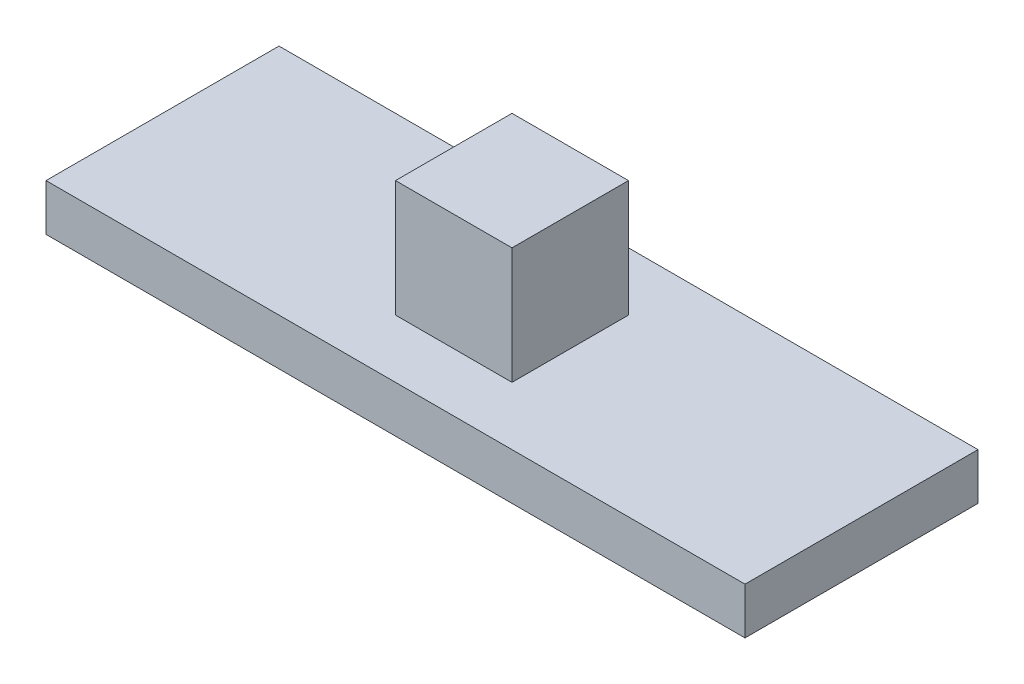
SolidWorks part; units mm, degrees
ref_plane "Front Plane" through (0, 0, 0) normal (0, 0, 1) x (1, 0, 0)
ref_plane "Top Plane" through (0, 0, 0) normal (0, 1, 0) x (1, 0, 0)
ref_plane "Right Plane" through (0, 0, 0) normal (1, 0, 0) x (0, 0, -1)
sketch "Sketch1" plane through (0, 0, 0) normal (0, 1, 0) x (1, 0, 0)
  line L1 (0, 0) -> (30, 0)
  line L2 (0, 0) -> (0, 10)
  line L3 (0, 10) -> (30, 10)
  line L4 (30, 0) -> (30, 10)
  dimension "D1" = 30
  dimension "D2" = 10
extrude "Boss-Extrude1" add sketch "Sketch1" along normal blind 2 contours L3 L4 L1 L2
sketch "Sketch2" plane through (0, 2, 0) normal (0, 1, 0) x (1, 0, 0)
  line L0 (0, 5) -> (30, 5) construction
  line L1 (17.5, 2.5) -> (12.5, 2.5)
  line L2 (17.5, 2.5) -> (17.5, 7.5)
  line L3 (17.5, 7.5) -> (12.5, 7.5)
  line L4 (12.5, 2.5) -> (12.5, 7.5)
  line L5 (17.5, 2.5) -> (12.5, 7.5) construction
  line L6 (17.5, 7.5) -> (12.5, 2.5) construction
  line L7 (0, 0) -> (0, 10) construction
  line L8 (30, 0) -> (30, 10) construction
  point P0 (15, 5)
  dimension "D1" = 5
  dimension "D2" = 15
  dimension "D3" = 5
extrude "Boss-Extrude2" add sketch "Sketch2" along normal blind 5 contours L3 L4 L1 L2
